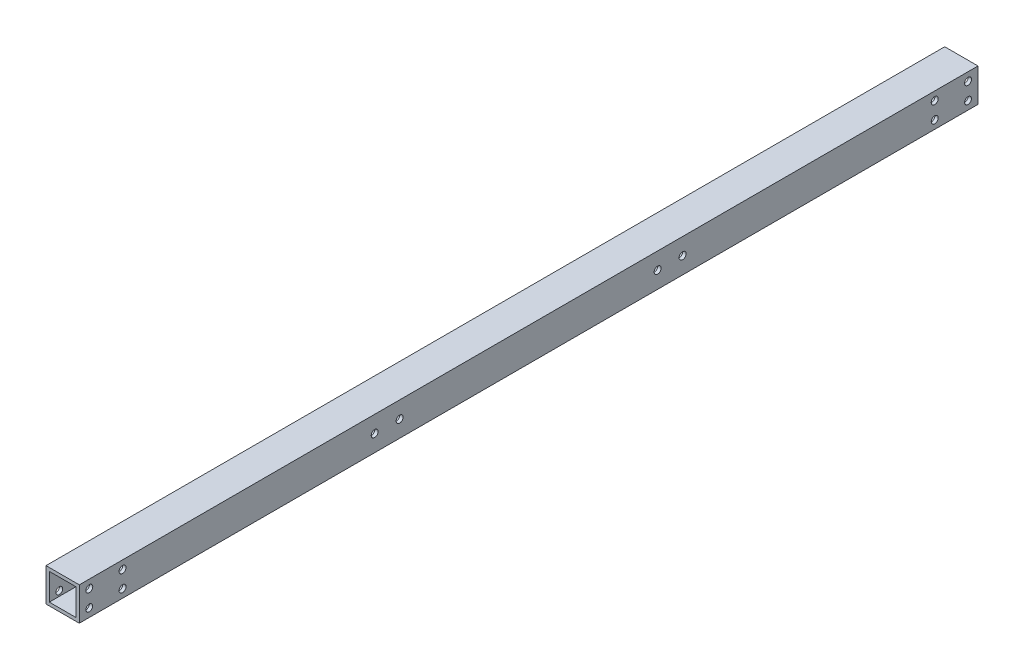
SolidWorks part; units mm, degrees
material "1060 合金"
ref_plane "前视基准面" through (0, 0, 0) normal (0, 0, 1) x (1, 0, 0)
ref_plane "上视基准面" through (0, 0, 0) normal (0, 1, 0) x (1, 0, 0)
ref_plane "右视基准面" through (0, 0, 0) normal (1, 0, 0) x (0, 0, -1)
sketch "草图1" plane through (0, 0, 0) normal (0, 0, 1) x (1, 0, 0)
  line L1 (-10, -10) -> (10, -10)
  line L2 (-10, -10) -> (-10, 10)
  line L3 (-10, 10) -> (10, 10)
  line L4 (10, -10) -> (10, 10)
  line L5 (-10, -10) -> (10, 10) construction
  line L6 (-10, 10) -> (10, -10) construction
  line L7 (-8, -8) -> (8, -8)
  line L8 (-8, -8) -> (-8, 8)
  line L9 (-8, 8) -> (8, 8)
  line L10 (8, -8) -> (8, 8)
  line L11 (-8, -8) -> (8, 8) construction
  line L12 (-8, 8) -> (8, -8) construction
  point P0 (0, 0)
  point P6 (0, 0)
  dimension "D1" = 20
  dimension "D2" = 20
  dimension "D3" = 2
extrude "凸台-拉伸1" add sketch "草图1" along normal blind 560
sketch "草图2" plane through (0, 0, 0) normal (0, 0, -1) x (-1, 0, 0)
  line L1 (-10, -10) -> (10, -10)
  line L2 (-10, -10) -> (-10, 10)
  line L3 (-10, 10) -> (10, 10)
  line L4 (10, -10) -> (10, 10)
extrude "切除-拉伸1" cut sketch "草图2" against normal blind 10
ref_plane "基准面1" through (-40, 280, 280) normal (0, 0, 1) x (0, -1, 0)
mirror "镜向1" about plane through (-40, 280, 280) normal (0, 0, 1) of "切除-拉伸1"
sketch "草图3" plane through (10, 0, 0) normal (1, 0, 0) x (0, 0, -1)
  line L0 (-280, -10) -> (-280, 31.2625) construction
  line L1 (-550, -10) -> (-10, -10) construction
  circle A0 centre (-16, 5) radius 2.1
  circle A1 centre (-16, -5) radius 2.0353
  circle A2 centre (-36, 5) radius 2.1
  circle A4 centre (-36, -5) radius 2.1
  circle A5 centre (-544, 5) radius 2.1
  circle A6 centre (-544, -5) radius 2.0353
  circle A7 centre (-524, -5) radius 2.1
  circle A8 centre (-524, 5) radius 2.1
extrude "切除-拉伸2" cut sketch "草图3" against normal through all
sketch "草图4" plane through (10, 0, 0) normal (1, 0, 0) x (0, 0, -1)
  line L0 (-180, 570) -> (-180, -10) construction
  line L1 (-210, 570) -> (-210, -10) construction
  line L2 (-550, 10) -> (-10, 10) construction
  line L3 (-280, -51.3022) -> (-280, 31.3022) construction
  circle A0 centre (-187.5, 0) radius 2.1
  circle A1 centre (-202.5, 0) radius 2.1
  circle A2 centre (-357.5, 0) radius 2.1
  circle A3 centre (-372.5, 0) radius 2.1
  point P16 (-280, -10)
  dimension "D1" = 4.2
  dimension "D2" = 4.2
  dimension "D3" = 7.5
  dimension "D4" = 7.5
  dimension "D5" = 10
extrude "切除-拉伸3" cut sketch "草图4" against normal through all
